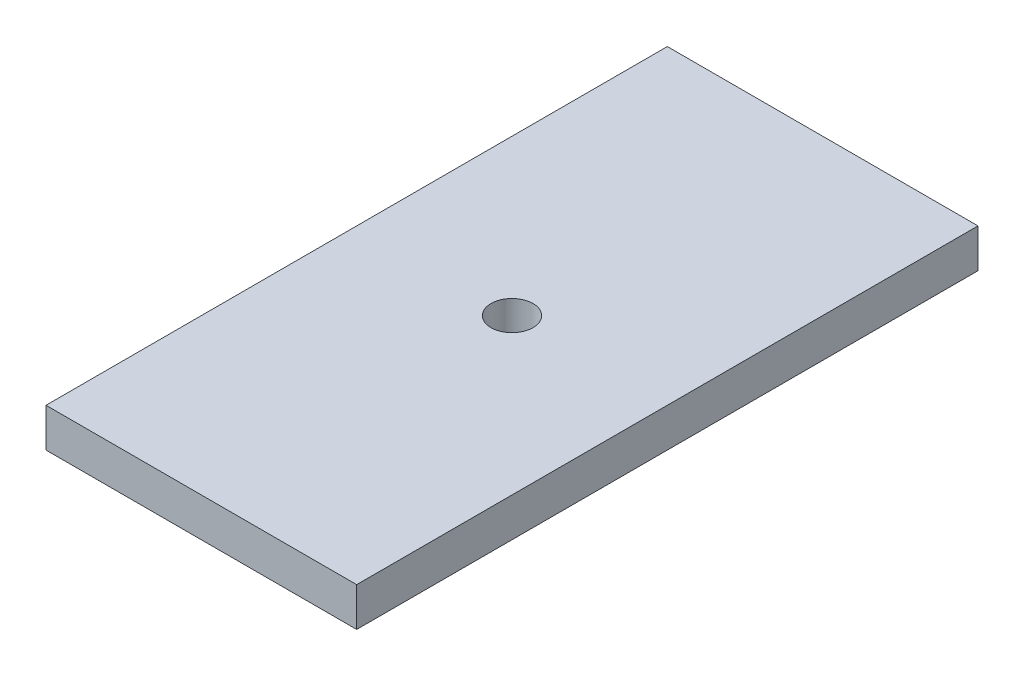
SolidWorks part; units mm, degrees
ref_plane "Front Plane" through (0, 0, 0) normal (0, 0, 1) x (1, 0, 0)
ref_plane "Top Plane" through (0, 0, 0) normal (0, 1, 0) x (1, 0, 0)
ref_plane "Right Plane" through (0, 0, 0) normal (1, 0, 0) x (0, 0, -1)
sketch "Sketch1" plane through (0, 0, 0) normal (0, 1, 0) x (1, 0, 0)
  line L1 (25.4, 50.8) -> (-25.4, 50.8)
  line L2 (25.4, 50.8) -> (25.4, -50.8)
  line L3 (25.4, -50.8) -> (-25.4, -50.8)
  line L4 (-25.4, 50.8) -> (-25.4, -50.8)
  line L5 (25.4, 50.8) -> (-25.4, -50.8) construction
  line L6 (25.4, -50.8) -> (-25.4, 50.8) construction
  circle A0 centre (0, 0) radius 3.429
  point P0 (0, 0)
  dimension "D3" = 6.858
  dimension "D1" = 50.8
  dimension "D2" = 101.6
extrude "Boss-Extrude1" add sketch "Sketch1" along normal blind 6.35
